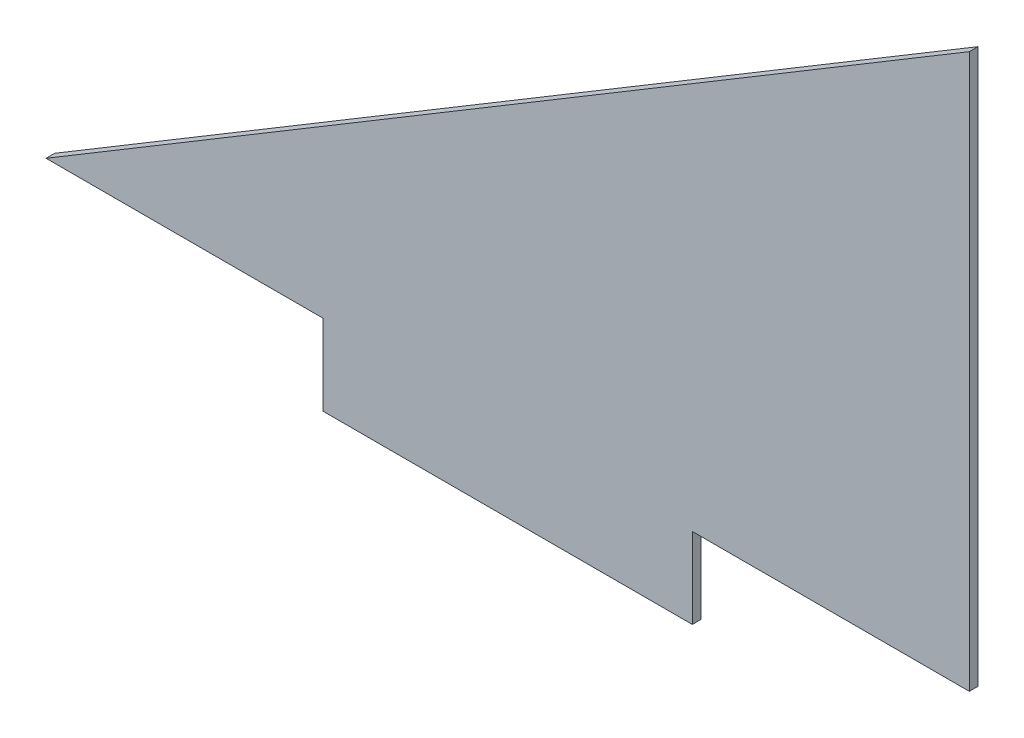
SolidWorks part; units mm, degrees
ref_plane "Front Plane" through (0, 0, 0) normal (0, 0, 1) x (1, 0, 0)
ref_plane "Top Plane" through (0, 0, 0) normal (0, 1, 0) x (1, 0, 0)
ref_plane "Right Plane" through (0, 0, 0) normal (1, 0, 0) x (0, 0, -1)
sketch "Sketch1" plane through (0, 0, 0) normal (0, 0, 1) x (1, 0, 0)
  line L0 (0, 0) -> (-76.2, 0)
  line L1 (-254, 0) -> (0, 152.4)
  line L2 (0, 152.4) -> (0, 0)
  line L3 (-177.8, 0) -> (-254, 0)
  line L5 (-177.8, 0) -> (-177.8, -22.1615)
  line L6 (-177.8, -22.1615) -> (-76.2, -22.1615)
  line L7 (-76.2, 0) -> (-76.2, -22.1615)
  dimension "D1" = 254
  dimension "D2" = 152.4
  dimension "D3" = 101.6
  dimension "D4" = 76.2
  dimension "D5" = 22.1615
extrude "Boss-Extrude1" add sketch "Sketch1" along normal blind 2.3876
